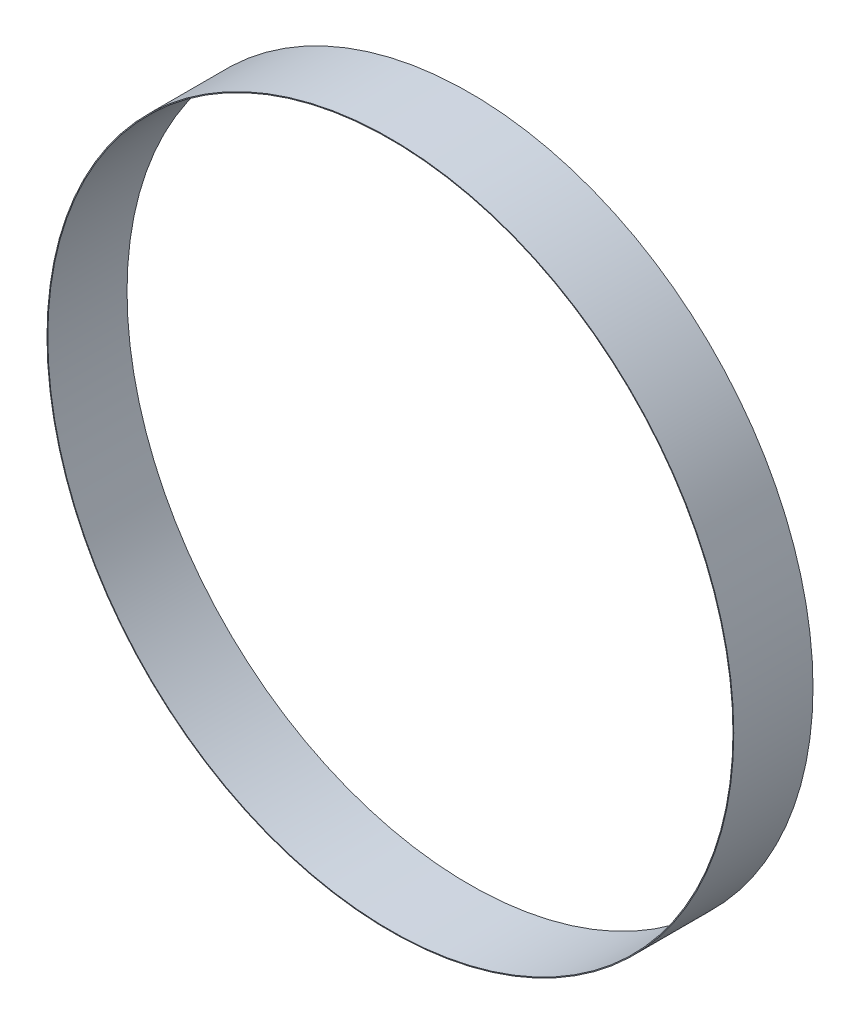
SolidWorks part; units mm, degrees
ref_plane "Front Plane" through (0, 0, 0) normal (0, 0, 1) x (1, 0, 0)
ref_plane "Top Plane" through (0, 0, 0) normal (0, 1, 0) x (1, 0, 0)
ref_plane "Right Plane" through (0, 0, 0) normal (1, 0, 0) x (0, 0, -1)
sketch "Sketch1" plane through (0, 0, 0) normal (0, 0, 1) x (1, 0, 0)
  circle A0 centre (0, 0) radius 1300
  dimension "D1" = 2600
extrude "Extrude-Thin1" add sketch "Sketch1" along normal mid plane 300 thin thin type one direction reverse wall 3
sketch "Sketch2" plane through (0, 0, 0) normal (0, 1, 0) x (1, 0, 0)
  line L0 (-702.4338, -90) -> (682.3642, -90) construction
  line L1 (-1300, -150) -> (1300, -150) construction
  text T0 "<i>JUNGLE</i>" font "Century Gothic" height 200
  point P3 (0, 0)
  point P4 (-702.4338, 0)
  point P6 (0, 0)
  dimension "D1" = 60
